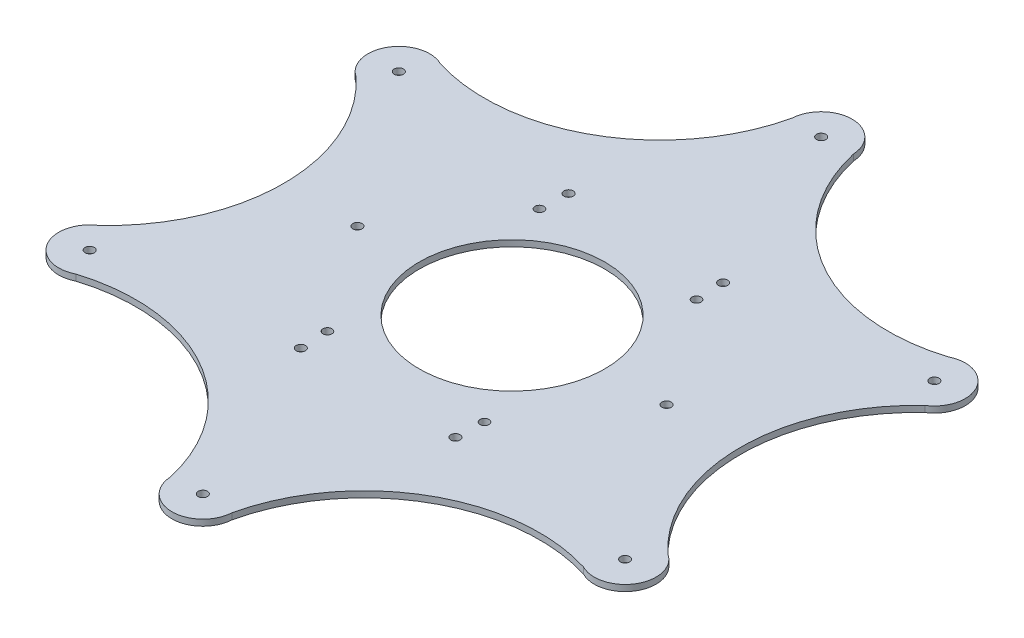
SolidWorks part; units mm, degrees
material "1060 Alloy"
ref_plane "Front Plane" through (0, 0, 0) normal (0, 0, 1) x (1, 0, 0)
ref_plane "Top Plane" through (0, 0, 0) normal (0, 1, 0) x (1, 0, 0)
ref_plane "Right Plane" through (0, 0, 0) normal (1, 0, 0) x (0, 0, -1)
sketch "Sketch1" plane through (0, 0, 0) normal (0, 1, 0) x (1, 0, 0)
  arc A0 (-92.0404, 41.6078) -> (-92.046, -41.6114) centre (-130.6349, 0.0008) cw
  arc A1 (-92.046, -41.6114) -> (-82.0536, -58.9055) centre (-86.6025, -50) ccw
  arc A2 (-82.0536, -58.9055) -> (-9.9865, -100.5199) centre (-65.3181, -113.1327) cw
  arc A3 (-9.9865, -100.5199) -> (9.9868, -100.5132) centre (0, -100) ccw
  arc A4 (9.9868, -100.5132) -> (82.0595, -58.9085) centre (65.3168, -113.1335) cw
  arc A5 (82.0595, -58.9085) -> (92.0404, -41.6078) centre (86.6025, -50) ccw
  arc A6 (92.0404, -41.6078) -> (92.046, 41.6114) centre (130.6349, -0.0008) cw
  arc A7 (92.046, 41.6114) -> (82.0536, 58.9055) centre (86.6025, 50) ccw
  arc A8 (82.0536, 58.9055) -> (9.9865, 100.5199) centre (65.3181, 113.1327) cw
  arc A9 (9.9865, 100.5199) -> (-9.9868, 100.5132) centre (0, 100) ccw
  arc A10 (-9.9868, 100.5132) -> (-82.0595, 58.9085) centre (-65.3168, 113.1335) cw
  arc A11 (-82.0595, 58.9085) -> (-92.0404, 41.6078) centre (-86.6025, 50) ccw
  circle A12 centre (86.6025, 50) radius 1.5
  circle A13 centre (86.6025, -50) radius 1.5
  circle A14 centre (0, -100) radius 1.5
  circle A15 centre (-86.6025, -50) radius 1.5
  circle A16 centre (-86.6025, 50) radius 1.5
  circle A17 centre (0, 100) radius 1.5
  circle A18 centre (-25, 43.3013) radius 1.5
  circle A19 centre (25, 43.3013) radius 1.5
  circle A20 centre (50, 0) radius 1.5
  circle A21 centre (25, -43.3013) radius 1.5
  circle A22 centre (-50, 0) radius 1.5
  circle A23 centre (-25, -43.3013) radius 1.5
extrude "Boss-Extrude1" add sketch "Sketch1" along normal blind 2
sketch "Sketch3" plane through (0, 0, 0) normal (0, -1, 0) x (-1, 0, 0)
  circle A0 centre (0, 0) radius 30
  dimension "D1" = 60
extrude "Cut-Extrude1" cut sketch "Sketch3" against normal through all
sketch "Sketch4" plane through (0, 2, 0) normal (0, 1, 0) x (1, 0, 0)
  line L1 (-25.4, -34.29) -> (25.4, -34.29) construction
  line L2 (-25.4, -34.29) -> (-25.4, 34.29) construction
  line L3 (-25.4, 34.29) -> (25.4, 34.29) construction
  line L4 (25.4, -34.29) -> (25.4, 34.29) construction
  line L5 (-25.4, -34.29) -> (25.4, 34.29) construction
  line L6 (-25.4, 34.29) -> (25.4, -34.29) construction
  point P0 (0, 0)
  dimension "D1" = 68.58
  dimension "D2" = 50.8
hole_wizard "M3.5 Tapped Hole1" positions "3DSketch1" profile "Sketch5" tap size "M3.5" standard "ISO" end condition through all
sketch3d "3DSketch1"
  point P0 (-25.4, 2, -34.29)
  point P3 (25.4, 2, -34.29)
  point P6 (25.4, 2, 34.29)
  point P9 (-25.4, 2, 34.29)
sketch "Sketch5" plane through (-25.4, 2, -34.29) normal (1, 0, 0) x (0, 0, 1)
  line L0 (0, 0) -> (0, 2)
  line L1 (0, 2) -> (1.45, 2)
  line L2 (1.45, 2) -> (1.45, 0)
  line L5 (1.45, 0) -> (0, 0)
  line L11 (0, -6.35) -> (0, 107.95) construction
  dimension "Thru Tap Drill Dia." = 2.9
  dimension "Thru Tap Drill Depth" = 2
cosmetic thread "Hole Thread1" parameters "D2"=3.5
cosmetic thread "Hole Thread2" parameters "D2"=3.5
cosmetic thread "Hole Thread3" parameters "D2"=3.5
cosmetic thread "Hole Thread4" parameters "D2"=3.5
